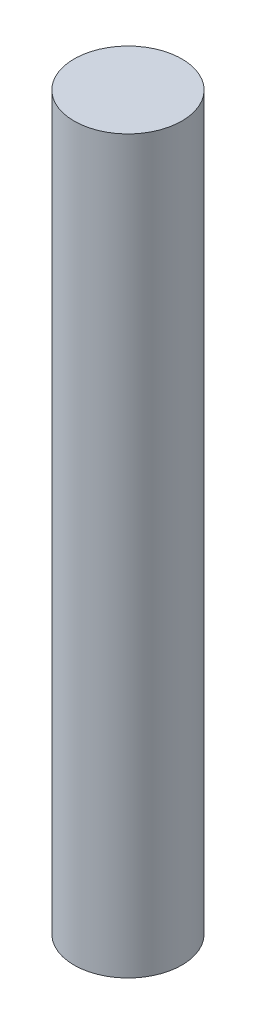
SolidWorks part; units mm, degrees
ref_plane "前视基准面" through (0, 0, 0) normal (0, 0, 1) x (1, 0, 0)
ref_plane "上视基准面" through (0, 0, 0) normal (0, 1, 0) x (1, 0, 0)
ref_plane "右视基准面" through (0, 0, 0) normal (1, 0, 0) x (0, 0, -1)
other "Configuration Table"
sketch "草图1" plane through (0, 0, 0) normal (0, 1, 0) x (1, 0, 0)
  circle A0 centre (0, 0) radius 1.4
  point P0 (-90.6464, 22.0667)
  dimension "D1" = 2.8
extrude "凸台-拉伸1" add sketch "草图1" along normal blind 19
